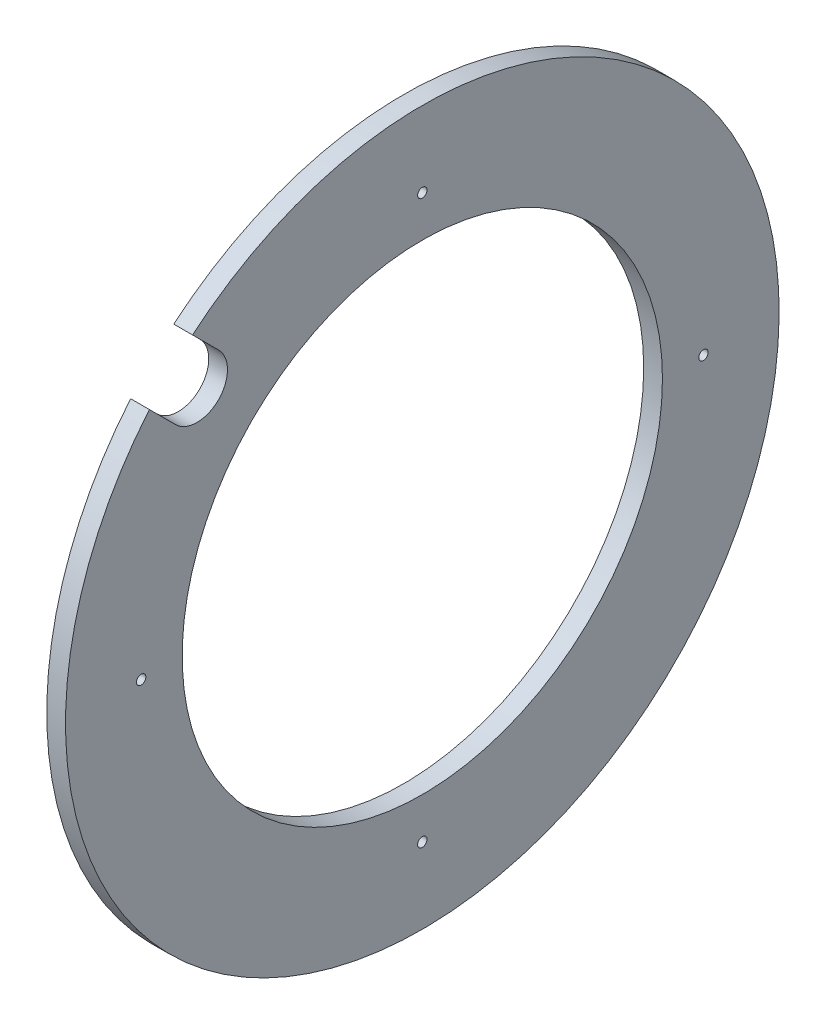
SolidWorks part; units mm, degrees
material "Teck"
ref_plane "Plan de face" through (0, 0, 0) normal (0, 0, 1) x (1, 0, 0)
ref_plane "Plan de dessus" through (0, 0, 0) normal (0, 1, 0) x (1, 0, 0)
ref_plane "Plan de droite" through (0, 0, 0) normal (1, 0, 0) x (0, 0, -1)
sketch "Esquisse1" plane through (0, 0, 0) normal (1, 0, 0) x (0, 0, -1)
  circle A0 centre (0, 0) radius 51.25
  circle A1 centre (0, 0) radius 76.15
  dimension "D1" = 102.5
  dimension "D2" = 152.3
extrude "Boss.-Extru.1" add sketch "Esquisse1" along normal blind 4
sketch "Sketch1" plane through (4, 0, 0) normal (1, 0, 0) x (0, 0, -1)
  circle A0 centre (0, 60) radius 1
  circle A1 centre (60, 0) radius 1
  circle A2 centre (0, -60) radius 1
  circle A3 centre (-60, 0) radius 1
  point P11 (0, 0)
  dimension "D2" = 2
  dimension "D3" = 60
  dimension "D1" = 4
extrude "air vents" cut sketch "Sketch1" against normal through all
sketch "Sketch2" plane through (4, 0, 0) normal (1, 0, 0) x (0, 0, -1)
  line L0 (0, 0) -> (-48.0833, 48.0833) construction
  line L1 (-43.4871, 52.6795) -> (-81.6004, 90.7927)
  line L2 (-52.6795, 43.4871) -> (-92.274, 83.0816)
  line L3 (-92.274, 83.0816) -> (-81.6004, 90.7927)
  line L4 (0, 0) -> (0, 42.3711) construction
  arc A0 (-52.6795, 43.4871) -> (-43.4871, 52.6795) centre (-48.0833, 48.0833) ccw
  dimension "D1" = 13
  dimension "D2" = 68
  dimension "D3" = 45
extrude "Cut-Extrude1" cut sketch "Sketch2" against normal blind 10
